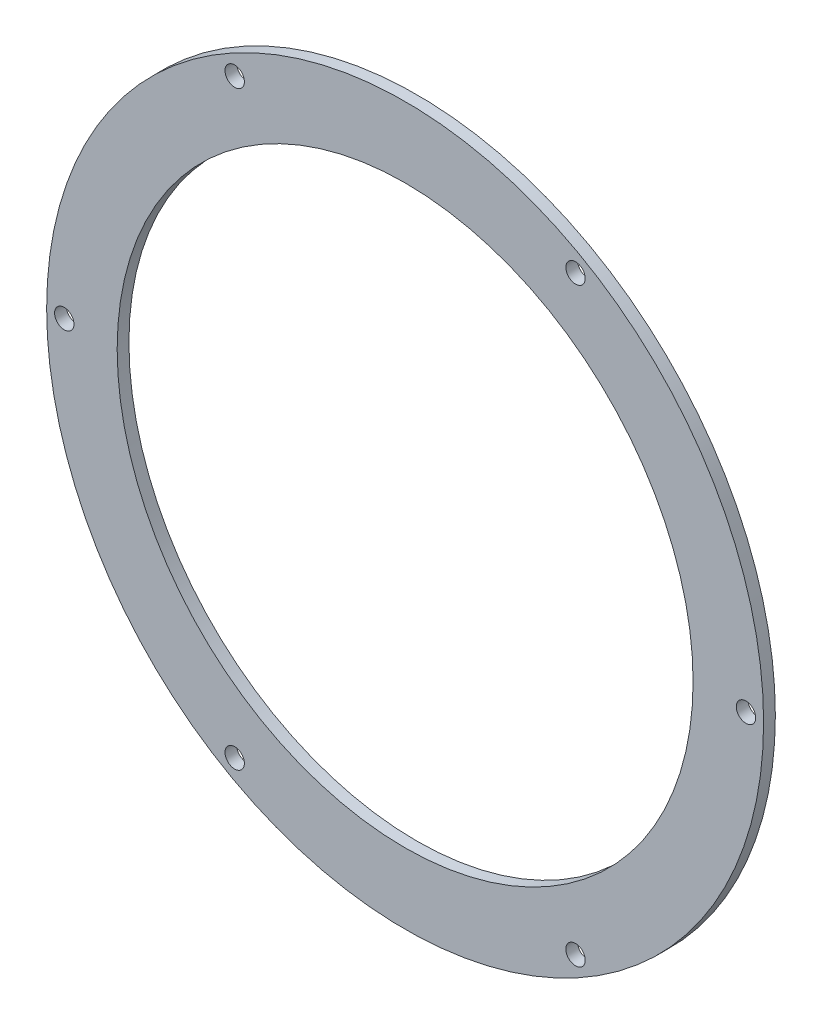
SolidWorks part; units mm, degrees
ref_plane "Спереди" through (0, 0, 0) normal (0, 0, 1) x (1, 0, 0)
ref_plane "Сверху" through (0, 0, 0) normal (0, 1, 0) x (1, 0, 0)
ref_plane "Справа" through (0, 0, 0) normal (1, 0, 0) x (0, 0, -1)
sketch "Эскиз1" plane through (0, 0, 0) normal (0, 0, 1) x (1, 0, 0)
  circle A0 centre (0, 0) radius 61
  circle A1 centre (0, 0) radius 49
extrude "Stator_clamp" add sketch "Эскиз1" along normal blind 2 from offset 15
sketch "Эскиз2" plane through (0, 0, 0) normal (0, 0, 1) x (1, 0, 0)
  circle A0 centre (58, 0) radius 1.65
  circle A1 centre (29, 50.2295) radius 1.65
  circle A2 centre (-29, 50.2295) radius 1.65
  circle A3 centre (-58, 0) radius 1.65
  circle A4 centre (-29, -50.2295) radius 1.65
  circle A5 centre (29, -50.2295) radius 1.65
extrude "Through_holes" cut sketch "Эскиз2" against normal mid plane 200
